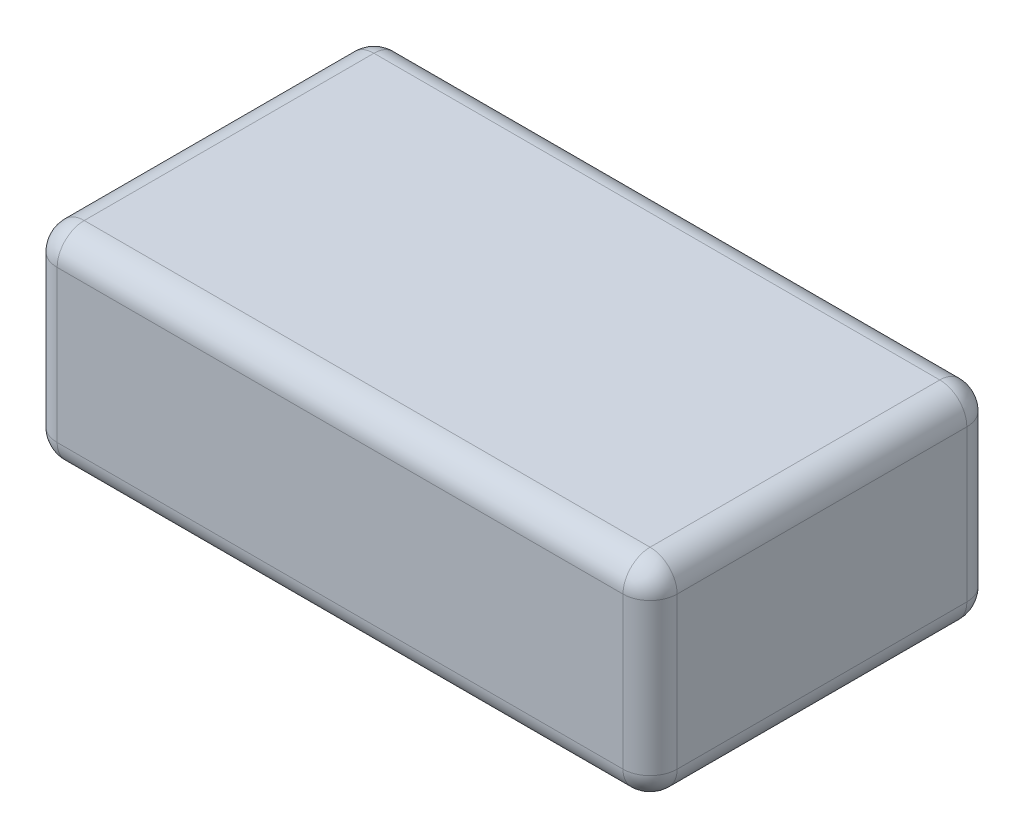
SolidWorks part; units mm, degrees
ref_plane "Front Plane" through (0, 0, 0) normal (0, 0, 1) x (1, 0, 0)
ref_plane "Top Plane" through (0, 0, 0) normal (0, 1, 0) x (1, 0, 0)
ref_plane "Right Plane" through (0, 0, 0) normal (1, 0, 0) x (0, 0, -1)
sketch "Sketch1" plane through (0, 0, 0) normal (0, 1, 0) x (1, 0, 0)
  line L1 (0, 0) -> (229, 0)
  line L2 (0, 0) -> (0, -127)
  line L3 (0, -127) -> (229, -127)
  line L4 (229, 0) -> (229, -127)
extrude "Boss-Extrude1" add sketch "Sketch1" along normal blind 76
fillet "Fillet1" radius 10 12 edges at (229, 0, 63.5) (229, 38, 0) (114.5, 0, 0) (0, 38, 0) (0, 0, 63.5) (114.5, 0, 127) (229, 38, 127) (0, 38, 127) (229, 76, 63.5) (114.5, 76, 0) (0, 76, 63.5) (114.5, 76, 127)
